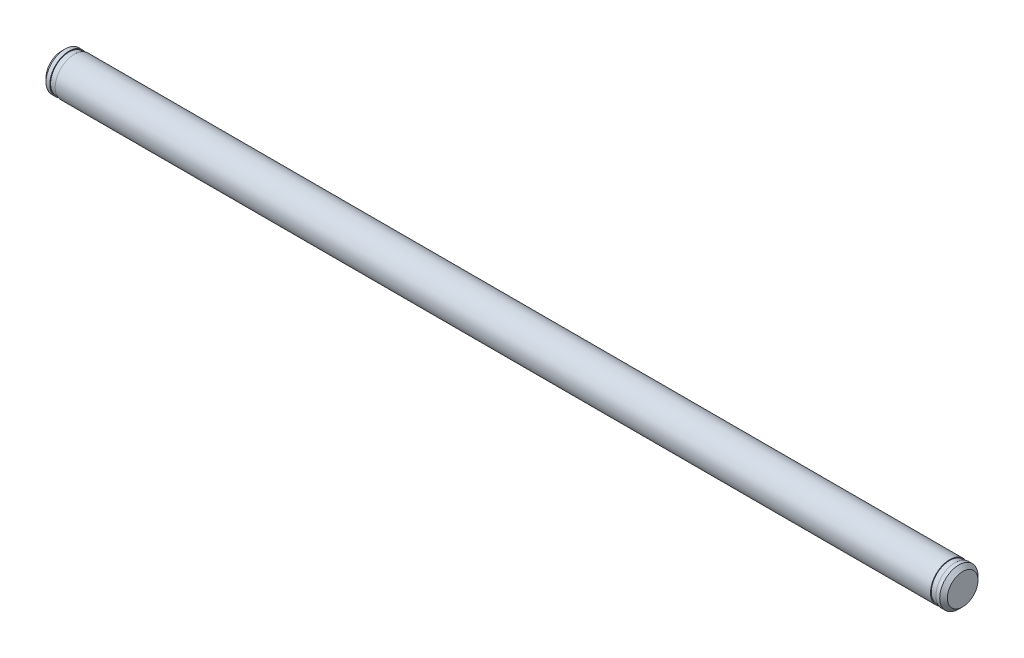
SolidWorks part; units mm, degrees
ref_plane "前视基准面" through (0, 0, 0) normal (0, 0, 1) x (1, 0, 0)
ref_plane "上视基准面" through (0, 0, 0) normal (0, 1, 0) x (1, 0, 0)
ref_plane "右视基准面" through (0, 0, 0) normal (1, 0, 0) x (0, 0, -1)
other "Configuration Table"
sketch "草图1" plane through (0, 0, 0) normal (0, 0, 1) x (1, 0, 0)
  line L0 (-0.2254, 0) -> (58.85, 0) construction
  line L1 (58.85, 0) -> (58.85, 2.5)
  line L2 (58.85, 2.5) -> (57.85, 2.5)
  line L3 (57.85, 2.5) -> (57.85, 2.4)
  line L4 (57.85, 2.4) -> (57.15, 2.4)
  line L5 (57.15, 2.4) -> (57.15, 2.5)
  line L6 (57.15, 2.5) -> (-57.15, 2.5)
  line L7 (0, 2.5) -> (0, 0) construction
  line L8 (0.2254, 0) -> (-58.85, 0) construction
  line L9 (-58.85, 0) -> (-58.85, 2.5)
  line L10 (-57.15, 2.4) -> (-57.15, 2.5)
  line L11 (-57.85, 2.4) -> (-57.15, 2.4)
  line L12 (-57.85, 2.5) -> (-57.85, 2.4)
  line L13 (-58.85, 2.5) -> (-57.85, 2.5)
  line L14 (58.85, 0) -> (-58.85, 0)
  line L15 (57.25, 2.4) -> (57.25, 0) construction
  line L16 (-57.25, 2.4) -> (-57.25, 0) construction
  dimension "D1" = 5
  dimension "D2" = 4.8
  dimension "D3" = 0.7
  dimension "D4" = 1
  dimension "D5" = 0.6
  dimension "D6" = 114.5
revolve "旋转1" add sketch "草图1" angle 360 about L14
chamfer "倒角1" distance 0.5 angle 45 2 edges at (58.85, 2.5, 0) (-58.85, 2.5, 0)
ref_plane "基准面1" through (-57.25, 0, 0) normal (-1, 0, 0) x (0, 0, 1)
